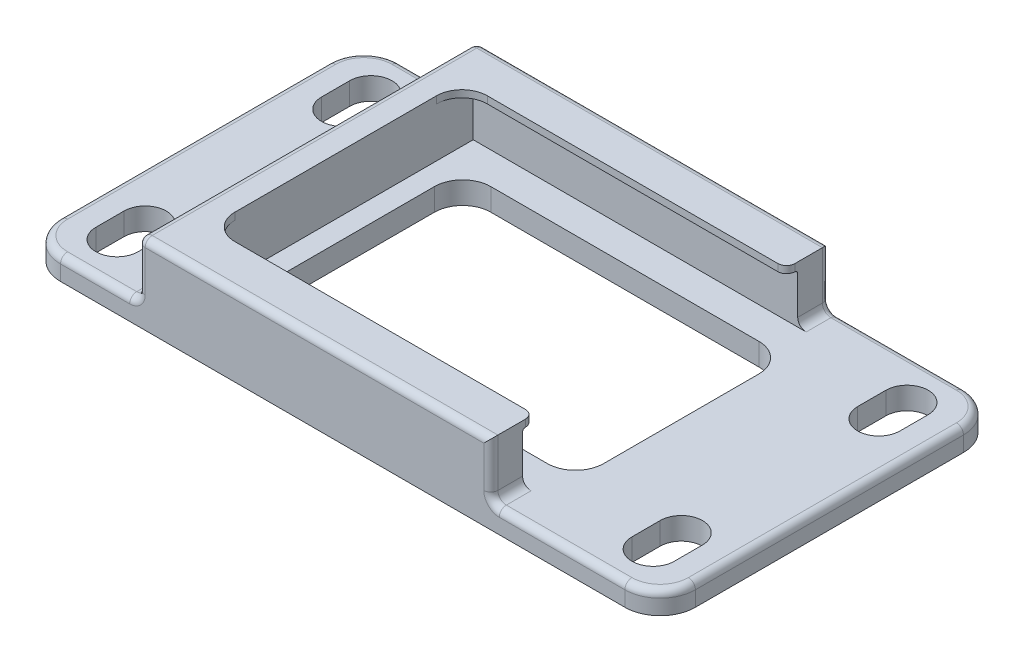
SolidWorks part; units mm, degrees
ref_plane "Front Plane" through (0, 0, 0) normal (0, 0, 1) x (1, 0, 0)
ref_plane "Top Plane" through (0, 0, 0) normal (0, 1, 0) x (1, 0, 0)
ref_plane "Right Plane" through (0, 0, 0) normal (1, 0, 0) x (0, 0, -1)
sketch "Sketch1" plane through (0, 0, 0) normal (0, 0, 1) x (1, 0, 0)
  line L0 (-28.575, 0) -> (-28.575, 2)
  line L1 (-28.575, 2) -> (-18.415, 2)
  line L6 (28.575, 2) -> (28.575, 0)
  line L7 (28.575, 0) -> (-28.575, 0)
  line L8 (-18.415, 2) -> (-18.415, 7.08)
  line L9 (-18.415, 7.08) -> (13.335, 7.08)
  line L10 (13.335, 7.08) -> (13.335, 2)
  line L11 (13.335, 2) -> (28.575, 2)
  point P9 (0, 0)
  dimension "D1" = 2
  dimension "D2" = 31.75
  dimension "D3" = 5.08
  dimension "D4" = 57.15
  dimension "D5" = 10.16
extrude "Boss-Extrude1" add sketch "Sketch1" along normal mid plane 30.48
sketch "Sketch4" plane through (0, 2, 0) normal (0, 1, 0) x (1, 0, 0)
  line L0 (24.13, 11.43) -> (24.13, 8.89) construction
  line L1 (26.035, 11.43) -> (26.035, 8.89)
  line L2 (22.225, 11.43) -> (22.225, 8.89)
  line L3 (24.13, -8.89) -> (24.13, -11.43) construction
  line L4 (26.035, -8.89) -> (26.035, -11.43)
  line L5 (22.225, -8.89) -> (22.225, -11.43)
  line L6 (-24.13, 11.43) -> (-24.13, 8.89) construction
  line L7 (-22.225, 11.43) -> (-22.225, 8.89)
  line L8 (-26.035, 11.43) -> (-26.035, 8.89)
  line L9 (-24.13, -8.89) -> (-24.13, -11.43) construction
  line L10 (-22.225, -8.89) -> (-22.225, -11.43)
  line L11 (-26.035, -8.89) -> (-26.035, -11.43)
  line L12 (28.575, -15.24) -> (28.575, 15.24) construction
  line L14 (-28.575, -15.24) -> (-28.575, 15.24) construction
  arc A4 (26.035, 11.43) -> (22.225, 11.43) centre (24.13, 11.43) ccw
  arc A5 (22.225, 8.89) -> (26.035, 8.89) centre (24.13, 8.89) ccw
  arc A6 (26.035, -8.89) -> (22.225, -8.89) centre (24.13, -8.89) ccw
  arc A7 (22.225, -11.43) -> (26.035, -11.43) centre (24.13, -11.43) ccw
  arc A8 (-22.225, 11.43) -> (-26.035, 11.43) centre (-24.13, 11.43) ccw
  arc A9 (-26.035, 8.89) -> (-22.225, 8.89) centre (-24.13, 8.89) ccw
  arc A10 (-22.225, -8.89) -> (-26.035, -8.89) centre (-24.13, -8.89) ccw
  arc A11 (-26.035, -11.43) -> (-22.225, -11.43) centre (-24.13, -11.43) ccw
  point P8 (24.13, 10.16)
  point P15 (24.13, -10.16)
  point P25 (-24.13, 10.16)
  point P32 (-24.13, -10.16)
  dimension "D2" = 3.81
  dimension "D3" = 4.445
  dimension "D5" = 2.54
  dimension "D6" = 2.54
  dimension "D8" = 4.445
  dimension "D9" = 20.32
  dimension "D10" = 10.16
  dimension "D11" = 2.54
  dimension "D12" = 2.54
extrude "Cut-Extrude1" cut sketch "Sketch4" against normal blind 19.05
sketch "Sketch5" plane through (13.335, 0, 0) normal (1, 0, 0) x (0, 0, -1)
  line L0 (-15.24, 2) -> (15.24, 2) construction
  line L1 (-12.3825, 2) -> (12.3825, 2)
  line L2 (-12.3825, 2) -> (-12.3825, 6.445)
  line L3 (-12.3825, 6.445) -> (-11.3665, 6.445)
  line L4 (-15.24, 7.08) -> (15.24, 7.08) construction
  line L5 (-11.3665, 7.08) -> (11.3665, 7.08)
  line L6 (-11.3665, 6.445) -> (-11.3665, 7.08)
  line L7 (12.3825, 2) -> (12.3825, 6.445)
  line L8 (12.3825, 6.445) -> (11.3665, 6.445)
  line L9 (11.3665, 6.445) -> (11.3665, 7.08)
  dimension "D1" = 24.765
  dimension "D2" = 12.3825
  dimension "D3" = 1.016
  dimension "D4" = 4.445
extrude "Cut-Extrude2" cut sketch "Sketch5" against normal offset from surface (29.21 mm away) 2.54 up to face at (-18.415, 4.54, 0)
sketch "Sketch7" plane through (0, 0, 0) normal (0, -1, 0) x (1, 0, 0)
  line L0 (-15.875, -12.3825) -> (-15.875, 12.3825) construction
  line L1 (-13.97, -9.525) -> (15.24, -9.525)
  line L2 (-13.97, -9.525) -> (-13.97, 9.525)
  line L3 (-13.97, 9.525) -> (15.24, 9.525)
  line L4 (15.24, -9.525) -> (15.24, 9.525)
  line L5 (-13.97, -9.525) -> (15.24, 9.525) construction
  line L6 (-13.97, 9.525) -> (15.24, -9.525) construction
  point P0 (0, 0)
  point P8 (0.635, 0)
  dimension "D1" = 29.21
  dimension "D2" = 19.05
  dimension "D3" = 15.875
  dimension "D4" = 16.51
extrude "Cut-Extrude4" cut sketch "Sketch7" against normal up to next
fillet "Fillet3" radius 2.54 4 edges at (-13.97, 1, 9.525) (-13.97, 1, -9.525) (15.24, 1, 9.525) (15.24, 1, -9.525)
fillet "Fillet6" radius 0.762 2 edges at (13.335, 6.7625, 11.3665) (13.335, 6.7625, -11.3665)
fillet "Fillet7" radius 2.286 2 edges at (-15.875, 6.7625, 11.3665) (-15.875, 6.7625, -11.3665)
fillet "Fillet9" radius 3.175 4 edges at (-28.575, 1, 15.24) (-28.575, 1, -15.24) (28.575, 1, 15.24) (28.575, 1, -15.24)
fillet "Fillet10" radius 0.762 3 edges at (13.335, 2, 13.8112) (13.335, 2, -13.8112) (-18.415, 2, 0)
fillet "Fillet11" radius 0.635 21 edges at (-2.54, 7.08, -15.24) (-2.54, 7.08, 15.24) (-18.415, 7.08, 0) (-18.6382, 2.2232, 15.24) (-22.2885, 2, 15.24) (-27.6451, 2, 14.3101) (-28.575, 2, 0) (-27.6451, 2, -14.3101) (-22.2885, 2, -15.24) (-18.6382, 2.2232, -15.24) (13.335, 4.921, -15.24) (13.5582, 2.2232, -15.24) (19.7485, 2, -15.24) (27.6451, 2, -14.3101) (28.575, 2, 0) (27.6451, 2, 14.3101) (13.335, 4.921, 15.24) (13.5582, 2.2232, 15.24) (-18.415, 4.921, 15.24) (-18.415, 4.921, -15.24) (19.7485, 2, 15.24)
fillet "Fillet12" radius 0.254 2 edges at (-1.27, 6.445, -12.3825) (-1.27, 6.445, 12.3825)
